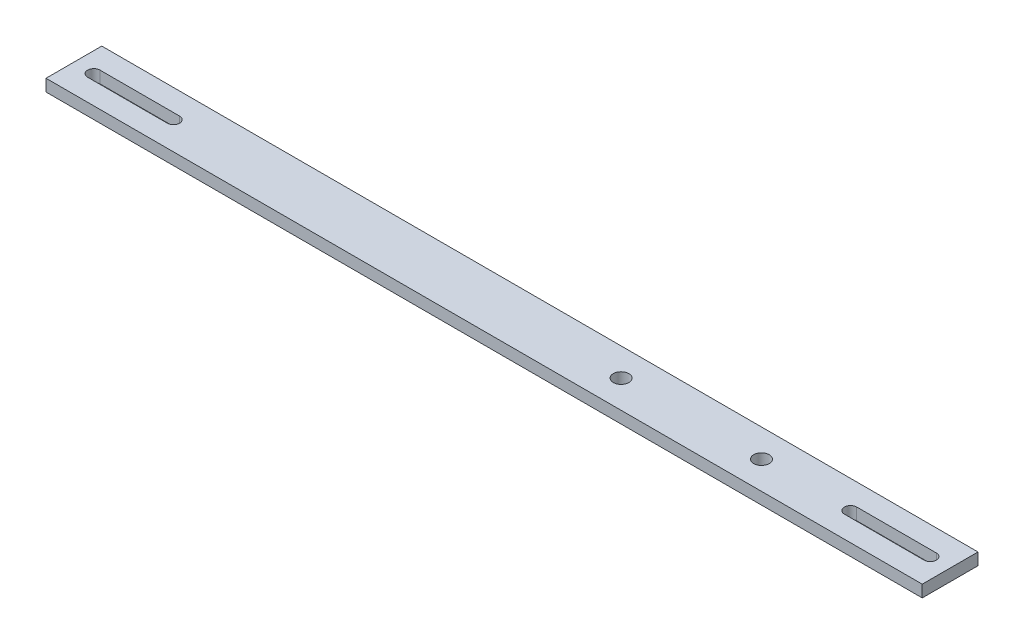
SolidWorks part; units mm, degrees
ref_plane "Front Plane" through (0, 0, 0) normal (0, 0, 1) x (1, 0, 0)
ref_plane "Top Plane" through (0, 0, 0) normal (0, 1, 0) x (1, 0, 0)
ref_plane "Right Plane" through (0, 0, 0) normal (1, 0, 0) x (0, 0, -1)
sketch "Skizze1" plane through (0, 0, 0) normal (0, 1, 0) x (1, 0, 0)
  line L1 (-110, -7) -> (110, -7)
  line L2 (-110, -7) -> (-110, 7)
  line L3 (-110, 7) -> (110, 7)
  line L4 (110, -7) -> (110, 7)
  line L5 (0, 7) -> (0, -7) construction
  line L6 (-110, 0) -> (110, 0) construction
  point P100 (0, 0)
  dimension "D1" = 14
  dimension "D2" = 220
extrude "Aufsatz-Linear austragen1" add sketch "Skizze1" along normal blind 3
sketch "Skizze2" plane through (0, 3, 0) normal (0, 1, 0) x (1, 0, 0)
  line L0 (110, 0) -> (45.5295, 0) construction
  line L1 (110, -7) -> (110, 7) construction
  line L2 (85, 0) -> (105, 0) construction
  line L3 (85, 1.55) -> (105, 1.55)
  line L4 (85, -1.55) -> (105, -1.55)
  arc A0 (85, 1.55) -> (85, -1.55) centre (85, 0) ccw
  arc A1 (105, -1.55) -> (105, 1.55) centre (105, 0) ccw
  point P7 (95, 0)
  dimension "D1" = 3.1
  dimension "D2" = 20
  dimension "D3" = 5
extrude "Schnitt-Linear austragen1" cut sketch "Skizze2" against normal through all
mirror "Spiegeln1" about plane through (0, 0, 0) normal (1, 0, 0) of "Schnitt-Linear austragen1"
sketch "Skizze3" plane through (0, 3, 0) normal (0, 1, 0) x (1, 0, 0)
  line L0 (110, 0) -> (62.633, 0) construction
  line L1 (110, -7) -> (110, 7) construction
  line L2 (110, 0) -> (27.383, 0) construction
  circle A0 centre (27.383, 0) radius 1.95
  circle A1 centre (62.633, 0) radius 1.95
  point P7 (27.383, 0)
  point P8 (62.633, 0)
  dimension "D4" = 3.9
  dimension "D5" = 3.9
  dimension "D1" = 47.367
  dimension "D2" = 82.617
  dimension "D3" = 35.25
extrude "Schnitt-Linear austragen2" cut sketch "Skizze3" against normal up to next
equation "\"D5@Skizze3\"=\"D4@Skizze3\""
